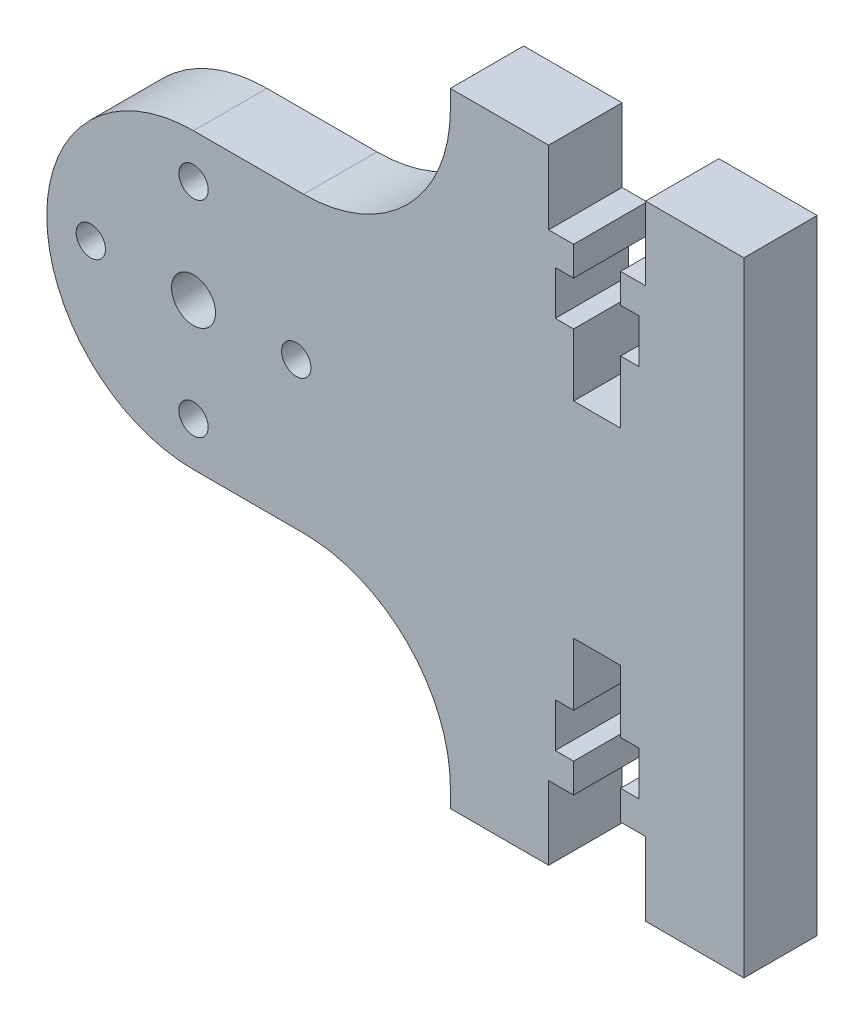
SolidWorks part; units mm, degrees
ref_plane "Plan de face" through (0, 0, 0) normal (0, 0, 1) x (1, 0, 0)
ref_plane "Plan de dessus" through (0, 0, 0) normal (0, 1, 0) x (1, 0, 0)
ref_plane "Plan de droite" through (0, 0, 0) normal (1, 0, 0) x (0, 0, -1)
sketch "Esquisse1" plane through (0, 0, 0) normal (0, 0, 1) x (1, 0, 0)
  line L0 (-12.9111, 37.8251) -> (-12.9111, -4.6749)
  line L1 (-12.9111, -4.6749) -> (-6.2111, -4.6749)
  line L2 (-6.2111, -4.6749) -> (-6.2111, 0.3251)
  line L3 (-6.2111, 0.3251) -> (-4.5111, 0.3251)
  line L4 (-4.5111, 0.3251) -> (-4.5111, 2.3218)
  line L5 (-4.5111, 2.3218) -> (-5.7611, 2.3218)
  line L6 (-5.7611, 2.3218) -> (-5.7611, 5.3218)
  line L7 (-5.7611, 5.3218) -> (-4.5111, 5.3218)
  line L8 (-4.5111, 5.3218) -> (-4.5111, 9.5751)
  line L9 (-4.5111, 9.5751) -> (-1.3111, 9.5751)
  line L10 (-1.3111, 9.5751) -> (-1.3111, 5.3218)
  line L11 (-1.3111, 5.3218) -> (-0.0611, 5.3218)
  line L12 (-0.0611, 5.3218) -> (-0.0611, 2.3218)
  line L13 (-0.0611, 2.3218) -> (-1.3111, 2.3218)
  line L14 (-1.3111, 2.3218) -> (-1.3111, 0.3251)
  line L15 (-1.3111, 0.3251) -> (0.3889, 0.3251)
  line L16 (0.3889, 0.3251) -> (0.3889, -4.6749)
  line L17 (0.3889, -4.6749) -> (7.0889, -4.6749)
  line L18 (7.0889, -4.6749) -> (7.0889, 37.8251)
  line L19 (-12.9111, 9.5751) -> (7.0889, 9.5751) construction
  line L20 (-12.9111, 16.5751) -> (7.0889, 16.5751) construction
  line L21 (-12.9111, 23.5751) -> (7.0889, 23.5751) construction
  line L22 (0.3889, 37.8251) -> (7.0889, 37.8251)
  line L23 (0.3889, 32.8251) -> (0.3889, 37.8251)
  line L24 (-1.3111, 32.8251) -> (0.3889, 32.8251)
  line L25 (-1.3111, 30.8284) -> (-1.3111, 32.8251)
  line L26 (-0.0611, 30.8284) -> (-1.3111, 30.8284)
  line L27 (-0.0611, 27.8284) -> (-0.0611, 30.8284)
  line L28 (-1.3111, 27.8284) -> (-0.0611, 27.8284)
  line L29 (-1.3111, 23.5751) -> (-1.3111, 27.8284)
  line L30 (-4.5111, 23.5751) -> (-1.3111, 23.5751)
  line L31 (-4.5111, 27.8284) -> (-4.5111, 23.5751)
  line L32 (-5.7611, 27.8284) -> (-4.5111, 27.8284)
  line L33 (-5.7611, 30.8284) -> (-5.7611, 27.8284)
  line L34 (-4.5111, 30.8284) -> (-5.7611, 30.8284)
  line L35 (-4.5111, 32.8251) -> (-4.5111, 30.8284)
  line L36 (-6.2111, 32.8251) -> (-4.5111, 32.8251)
  line L37 (-6.2111, 37.8251) -> (-6.2111, 32.8251)
  line L38 (-12.9111, 37.8251) -> (-6.2111, 37.8251)
  dimension "D1" = 21.25
  dimension "D2" = 21.25
  dimension "D3" = 20
  dimension "D4" = 6.7
  dimension "D5" = 6.7
  dimension "D6" = 3.2
  dimension "D7" = 1.7
  dimension "D8" = 7
  dimension "D9" = 3.2
  dimension "D10" = 0
  dimension "D11" = 5.7
  dimension "D12" = 1.25
  dimension "D13" = 1.9967
  dimension "D14" = 1.9967
  dimension "D15" = 3
  dimension "D16" = 3
  dimension "D17" = 5
  dimension "D18" = 5
extrude "Boss.-Extru.1" add sketch "Esquisse1" along normal blind 5
sketch "Esquisse2" plane through (0, 0, 0) normal (0, 0, -1) x (-1, 0, 0)
  line L12 (12.9111, 37.8251) -> (12.9111, -4.6749) construction
  line L14 (30.4111, 26.5751) -> (12.9111, 26.5751)
  line L16 (30.4111, 6.5751) -> (12.9111, 6.5751)
  line L17 (12.9111, 26.5751) -> (12.9111, 6.5751)
  arc A16 (30.4111, 6.5751) -> (30.4111, 26.5751) centre (30.4111, 16.5751) ccw
  circle A17 centre (30.4111, 16.5751) radius 1.5
  circle A18 centre (30.4111, 23.5751) radius 1
  circle A19 centre (23.4111, 16.5751) radius 1
  circle A20 centre (30.4111, 9.5751) radius 1
  circle A21 centre (37.4111, 16.5751) radius 1
  point P51 (12.9111, 16.5751)
  dimension "D2" = 20
  dimension "D3" = 3
  dimension "D4" = 17.5
  dimension "D5" = 2
  dimension "D6" = 2
  dimension "D7" = 2
  dimension "D8" = 2
  dimension "D1" = 7
  dimension "D9" = 7
  dimension "D10" = 7
  dimension "D11" = 7
extrude "Boss.-Extru.2" add sketch "Esquisse2" against normal up to vertex (5 mm away)
fillet "Congé1" radius 10 2 edges at (-12.9111, 6.5751, 2.5) (-12.9111, 26.5751, 2.5)
